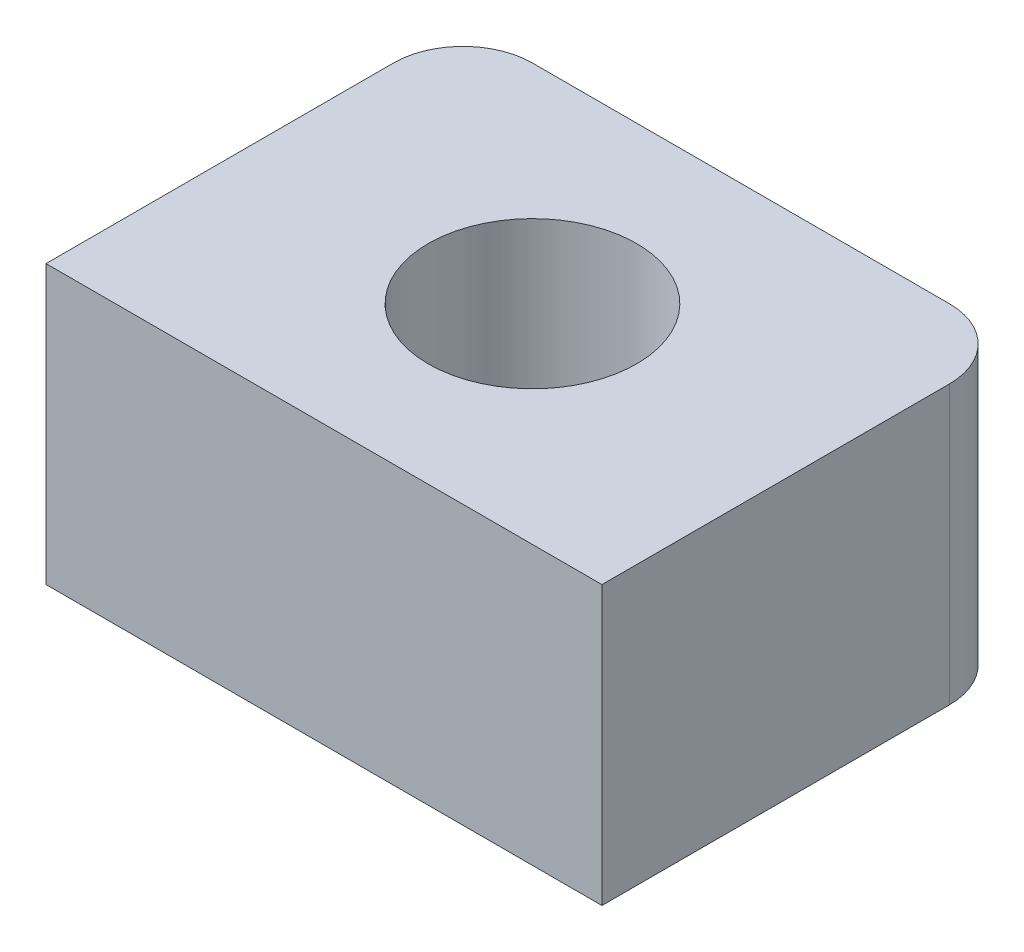
SolidWorks part; units mm, degrees
ref_plane "Front Plane" through (0, 0, 0) normal (0, 0, 1) x (1, 0, 0)
ref_plane "Top Plane" through (0, 0, 0) normal (0, 1, 0) x (1, 0, 0)
ref_plane "Right Plane" through (0, 0, 0) normal (1, 0, 0) x (0, 0, -1)
sketch "Sketch1" plane through (0, 0, 0) normal (0, 1, 0) x (1, 0, 0)
  line L1 (0, 0) -> (25.4, 0)
  line L2 (0, 0) -> (0, 19.05)
  line L3 (0, 19.05) -> (25.4, 19.05)
  line L4 (25.4, 0) -> (25.4, 19.05)
  dimension "D1" = 25.4
  dimension "D2" = 19.05
extrude "Boss-Extrude1" add sketch "Sketch1" along normal blind 12.7
sketch "Sketch2" plane through (0, 12.7, 0) normal (0, 1, 0) x (1, 0, 0)
  line L0 (12.7, 19.05) -> (12.7, 0) construction
  line L1 (25.4, 19.05) -> (0, 19.05) construction
  line L2 (0, 0) -> (25.4, 0) construction
  line L3 (12.7, 0) -> (25.4, 9.525) construction
  line L4 (25.4, 0) -> (25.4, 19.05) construction
  line L5 (25.4, 9.525) -> (0, 9.525) construction
  line L6 (0, 19.05) -> (0, 0) construction
  circle A0 centre (12.7, 9.525) radius 4.7625
extrude "Cut-Extrude1" cut sketch "Sketch2" against normal through all
fillet "Fillet1" radius 3.175 2 edges at (0, 6.35, -19.05) (25.4, 6.35, -19.05)
